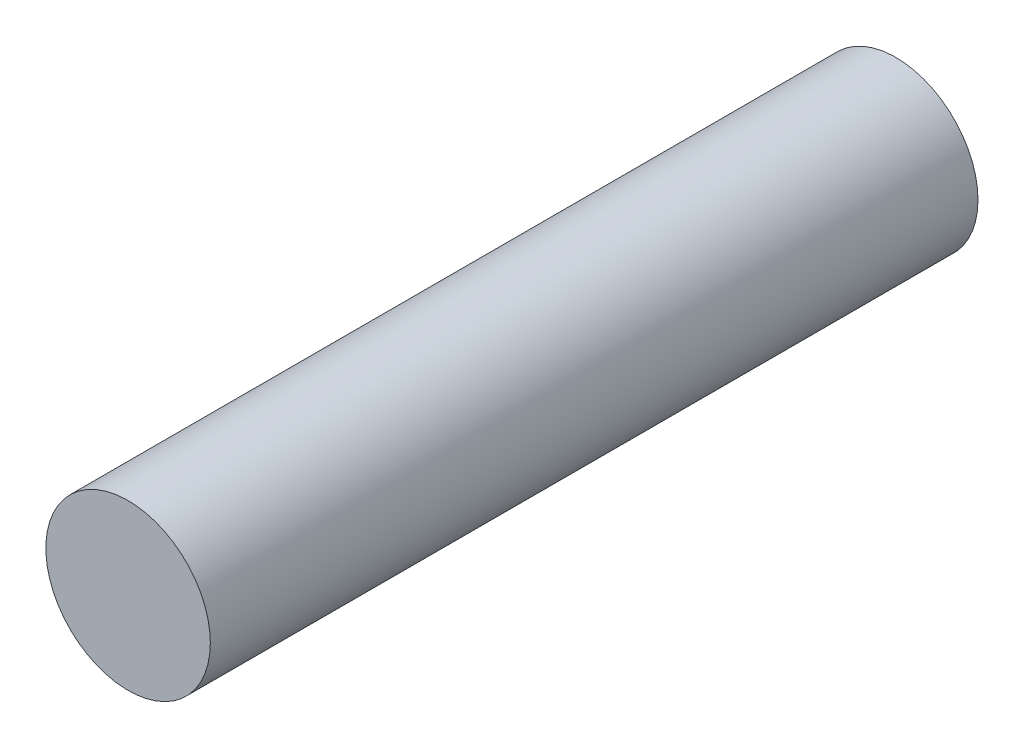
SolidWorks part; units mm, degrees
ref_plane "前视基准面" through (0, 0, 0) normal (0, 0, 1) x (1, 0, 0)
ref_plane "上视基准面" through (0, 0, 0) normal (0, 1, 0) x (1, 0, 0)
ref_plane "右视基准面" through (0, 0, 0) normal (1, 0, 0) x (0, 0, -1)
sketch "草图1" plane through (0, 0, 0) normal (0, 0, 1) x (1, 0, 0)
  circle A0 centre (0, 0) radius 3
  dimension "D1" = 6
extrude "凸台-拉伸1" add sketch "草图1" along normal blind 28
